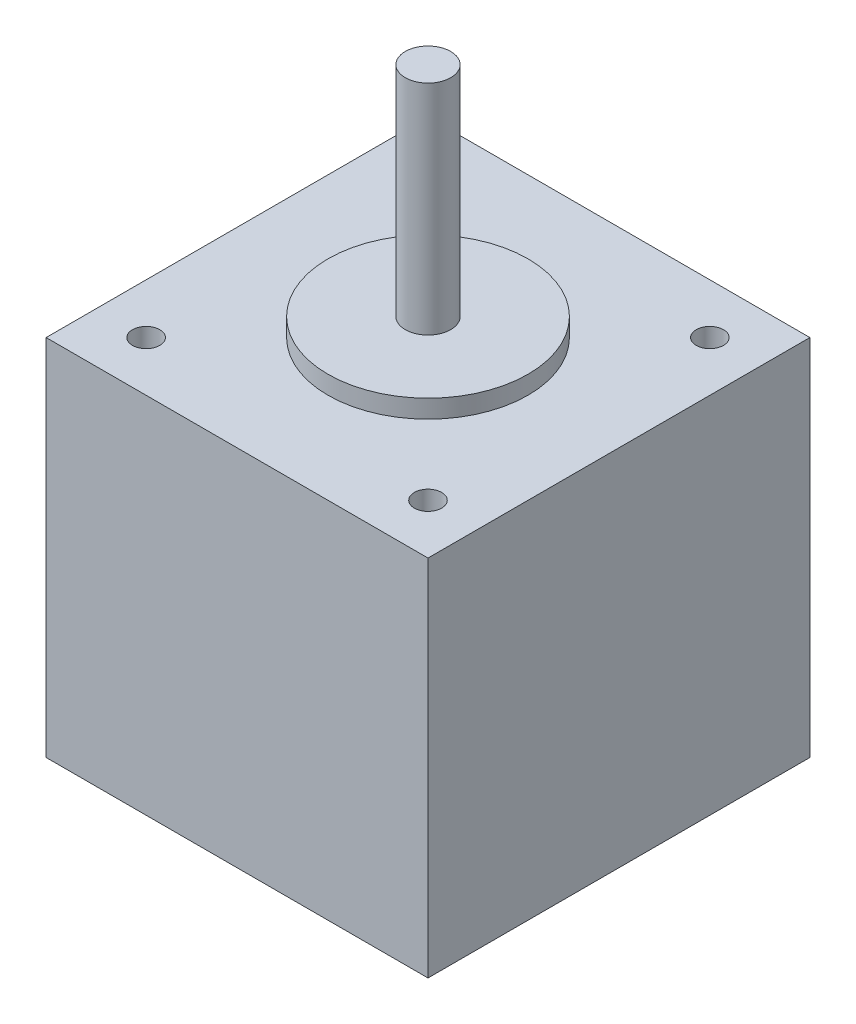
SolidWorks part; units mm, degrees
ref_plane "정면" through (0, 0, 0) normal (0, 0, 1) x (1, 0, 0)
ref_plane "윗면" through (0, 0, 0) normal (0, 1, 0) x (1, 0, 0)
ref_plane "우측면" through (0, 0, 0) normal (1, 0, 0) x (0, 0, -1)
sketch "스케치1" plane through (0, 0, 0) normal (0, 1, 0) x (1, 0, 0)
  line L1 (-21, -21) -> (21, -21)
  line L2 (-21, -21) -> (-21, 21)
  line L3 (-21, 21) -> (21, 21)
  line L4 (21, -21) -> (21, 21)
  line L5 (-21, -21) -> (21, 21) construction
  line L6 (-21, 21) -> (21, -21) construction
  point P0 (0, 0)
  dimension "D1" = 42
  dimension "D2" = 42
extrude "보스-돌출1" add sketch "스케치1" along normal blind 40
sketch "스케치3" plane through (0, 40, 0) normal (0, 1, 0) x (1, 0, 0)
  circle A0 centre (-15.5, 15.5) radius 1.5
  circle A1 centre (15.5, 15.5) radius 1.5
  circle A2 centre (15.5, -15.5) radius 1.5
  circle A3 centre (-15.5, -15.5) radius 1.5
  point P12 (0, 0)
  dimension "D1" = 3
  dimension "D4" = 4
  dimension "D2" = 15.5
  dimension "D3" = 15.5
extrude "컷-돌출1" cut sketch "스케치3" against normal through all
sketch "스케치4" plane through (0, 40, 0) normal (0, 1, 0) x (1, 0, 0)
  circle A0 centre (0, 0) radius 11
  dimension "D1" = 22
extrude "보스-돌출2" add sketch "스케치4" along normal blind 2
sketch "스케치5" plane through (0, 42, 0) normal (0, 1, 0) x (1, 0, 0)
  circle A0 centre (0, 0) radius 2.5
  dimension "D1" = 5
extrude "보스-돌출3" add sketch "스케치5" along normal blind 24
